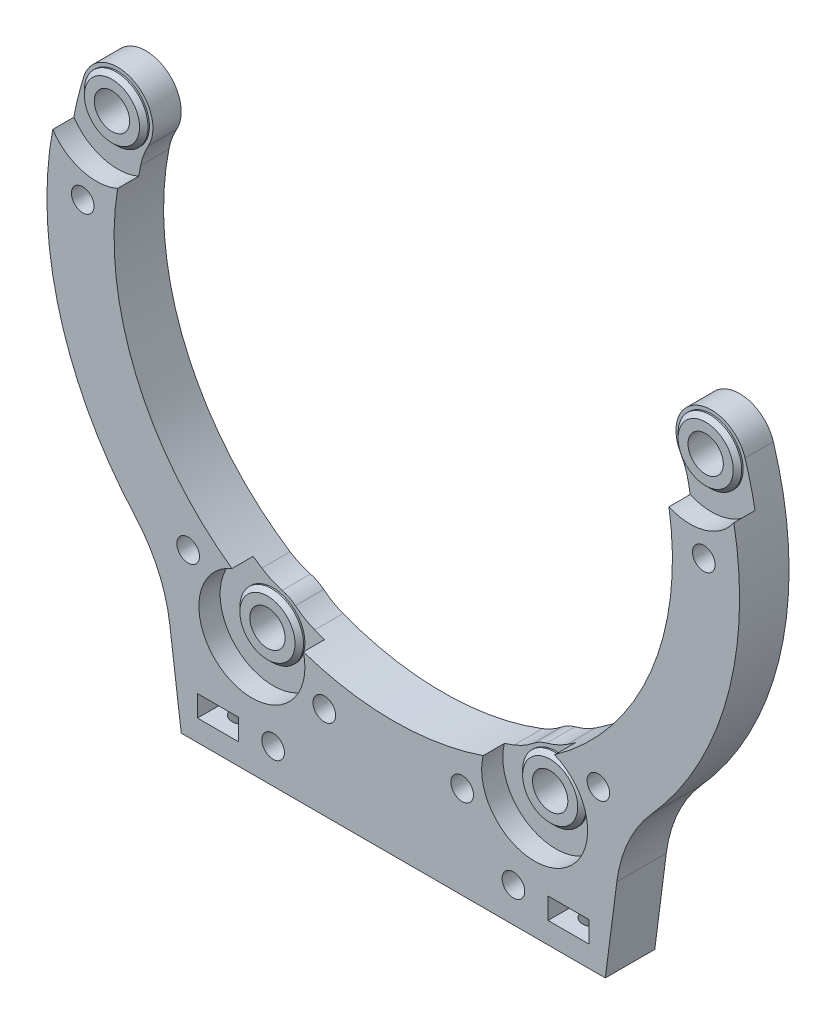
SolidWorks part; units mm, degrees
ref_plane "Front Plane" through (0, 0, 0) normal (0, 0, 1) x (1, 0, 0)
ref_plane "Top Plane" through (0, 0, 0) normal (0, 1, 0) x (1, 0, 0)
ref_plane "Right Plane" through (0, 0, 0) normal (1, 0, 0) x (0, 0, -1)
sketch "Sketch1" plane through (0, 0, 0) normal (0, 0, 1) x (1, 0, 0)
  line L0 (-74.8664, -56) -> (73.8479, -56) construction
  line L1 (-42, 13.1149) -> (42, 13.1149) construction
  line L2 (-20, -39.1918) -> (20, -39.1918) construction
  line L3 (37, 0) -> (37, 13.1149) construction
  line L4 (30, -56) -> (32.5, -36.6708)
  line L5 (-30, -56) -> (30, -56)
  line L6 (-30, -56) -> (-32.5, -36.6708)
  line L7 (0, -56) -> (0, 0) construction
  circle A0 centre (0, 0) radius 37 construction
  circle A1 centre (42, 13.1149) radius 7 construction
  circle A2 centre (-42, 13.1149) radius 7 construction
  circle A3 centre (-20, -39.1918) radius 7 construction
  circle A4 centre (20, -39.1918) radius 7 construction
  circle A5 centre (42, 13.1149) radius 5
  circle A6 centre (-42, 13.1149) radius 5
  circle A7 centre (-20, -39.1918) radius 5
  circle A8 centre (20, -39.1918) radius 5
  circle A9 centre (-42, 13.1149) radius 2.5
  circle A10 centre (42, 13.1149) radius 2.5
  circle A11 centre (20, -39.1918) radius 2.5
  circle A12 centre (-20, -39.1918) radius 2.5
  circle A13 centre (0, 0) radius 39.5
  circle A14 centre (0, 0) radius 49
  dimension "D1" = 74
  dimension "D3" = 14
  dimension "D4" = 10
  dimension "D6" = 5
  dimension "D7" = 79
  dimension "D2" = 19
  dimension "D5" = 40
  dimension "D8" = 60
  dimension "D9" = 65
extrude "Boss-Extrude1" add sketch "Sketch1" along normal blind 4 contours A6 A14 A7 A13 | A13 A6 A9 | A6 A13 | A8 A14 A5 A13 | A13 A5 A10 | A5 A13 | A13 A7 A12 | A7 A13 | A13 A8 A11 | A8 A13 | A7 A14 A8 A13 | A14 L6 L5 L4
sketch "Sketch2" plane through (0, 0, 4) normal (0, 0, 1) x (1, 0, 0)
  circle A0 centre (-42, 13.1149) radius 4.5
  circle A1 centre (-42, 13.1149) radius 2.5 construction
  circle A2 centre (-42, 13.1149) radius 2.5
  circle A3 centre (42, 13.1149) radius 4.5
  circle A4 centre (42, 13.1149) radius 2.5 construction
  circle A5 centre (42, 13.1149) radius 2.5
  circle A6 centre (-20, -39.1918) radius 2.5 construction
  circle A7 centre (-20, -39.1918) radius 2.5
  circle A8 centre (-20, -39.1918) radius 4.5
  circle A9 centre (20, -39.1918) radius 2.5 construction
  circle A10 centre (20, -39.1918) radius 2.5
  circle A11 centre (20, -39.1918) radius 4.5
  dimension "D1" = 9
extrude "Boss-Extrude2" add sketch "Sketch2" along normal blind 0.8
chamfer "Chamfer1" distance 0.6 angle 45 4 edges at (-15.5, -39.1918, 4.8) (24.5, -39.1918, 4.8) (46.5, 13.1149, 4.8) (-37.5, 13.1149, 4.8)
sketch "Sketch3" plane through (0, 0, 4) normal (0, 0, 1) x (1, 0, 0)
  line L0 (-30, -56) -> (-32.5, -36.6708) construction
  line L1 (-30, -56) -> (30, -56) construction
  line L2 (30, -56) -> (32.5, -36.6708) construction
  line L3 (-30, -56) -> (-32.5, -36.6708)
  line L4 (-30, -56) -> (30, -56)
  line L5 (30, -56) -> (32.5, -36.6708)
  circle A0 centre (-42, 13.1149) radius 7.5
  circle A1 centre (42, 13.1149) radius 7.5
  circle A2 centre (20, -39.1918) radius 7.5
  circle A3 centre (-20, -39.1918) radius 7.5
  arc A4 (32.5, -36.6708) -> (46.7727, 14.6052) centre (0, 0) ccw construction
  arc A5 (19.7687, -34.1972) -> (38.2683, 9.787) centre (0, 0) ccw construction
  arc A6 (-16.0913, -36.0738) -> (16.0913, -36.0738) centre (0, 0) ccw construction
  arc A7 (-46.7727, 14.6052) -> (-32.5, -36.6708) centre (0, 0) ccw construction
  arc A8 (-38.2683, 9.787) -> (-19.7687, -34.1972) centre (0, 0) ccw construction
  arc A9 (32.5, -36.6708) -> (46.7727, 14.6052) centre (0, 0) ccw
  arc A10 (19.7687, -34.1972) -> (38.2683, 9.787) centre (0, 0) ccw
  arc A11 (-16.0913, -36.0738) -> (16.0913, -36.0738) centre (0, 0) ccw
  arc A12 (-46.7727, 14.6052) -> (-32.5, -36.6708) centre (0, 0) ccw
  arc A13 (-38.2683, 9.787) -> (-19.7687, -34.1972) centre (0, 0) ccw
  arc M5 (38.2683, 9.787) -> (19.7687, -34.1972) centre (0, 0) cw
  arc M7 (16.0913, -36.0738) -> (-16.0913, -36.0738) centre (0, 0) cw
  arc M9 (-19.7687, -34.1972) -> (-38.2683, 9.787) centre (0, 0) cw
  arc M11 (-46.7727, 14.6052) -> (-32.5, -36.6708) centre (0, 0) ccw
  line M12 (-32.5, -36.6708) -> (-30, -56)
  line M13 (-30, -56) -> (30, -56)
  line M14 (30, -56) -> (32.5, -36.6708)
  arc M15 (32.5, -36.6708) -> (46.7727, 14.6052) centre (0, 0) ccw
  dimension "D1" = 15
extrude "Boss-Extrude3" add sketch "Sketch3" along normal blind 3 contours A3 A0 A1 A2 M9 M11 M12 M13 M14 M15 M5 M7
fillet "Fillet1" radius 10 6 edges at (-19.7687, -34.1972, 2) (-16.0913, -36.0738, 2) (16.0913, -36.0738, 2) (19.7687, -34.1972, 2) (38.2683, 9.787, 2) (-38.2683, 9.787, 2)
fillet "Fillet2" radius 20 2 edges at (32.5, -36.6708, 3.5) (-32.5, -36.6708, 3.5)
sketch "Sketch4" plane through (0, -56, 0) normal (0, -1, 0) x (1, 0, 0)
  line L4 (24.8, 10.5) -> (-24.8, 10.5)
  line L5 (24.8, 3.4) -> (24.8, 10.5)
  line L6 (-24.8, 3.4) -> (24.8, 3.4)
  line L7 (-24.8, 10.5) -> (-24.8, 3.4)
  line L8 (24.8, 10.5) -> (-24.8, 10.5) construction
  line L9 (24.8, 3.4) -> (24.8, 10.5) construction
  line L10 (-24.8, 3.4) -> (24.8, 3.4) construction
  line L11 (-24.8, 10.5) -> (-24.8, 3.4) construction
  circle A1 centre (24.8, 3.4) radius 1.6
  circle A2 centre (24.8, 3.4) radius 1.6
  circle A3 centre (-24.8, 3.4) radius 1.6
  circle A4 centre (-24.8, 3.4) radius 1.6
  circle A5 centre (24.8, 10.5) radius 1.6
  circle A6 centre (24.8, 10.5) radius 1.6 construction
  circle A7 centre (-24.8, 10.5) radius 1.6
  circle A8 centre (-24.8, 10.5) radius 1.6 construction
  dimension "D1" = 0
  dimension "D2" = 0
  dimension "D3" = 0
  dimension "D4" = 0
  dimension "D5" = 0
extrude "Cut-Extrude1" cut sketch "Sketch4" against normal blind 9
sketch "Sketch5" plane through (0, 0, 7) normal (0, 0, 1) x (1, 0, 0)
  line L5 (-27.7, -50) -> (-27.7, -53)
  line L6 (-21.9, -50) -> (-27.7, -50)
  line L7 (-21.9, -53) -> (-21.9, -50)
  line L8 (-27.7, -53) -> (-21.9, -53)
  line L9 (-27.7, -50) -> (-27.7, -53)
  line L10 (-21.9, -50) -> (-27.7, -50)
  line L11 (-21.9, -53) -> (-21.9, -50)
  line L12 (-27.7, -53) -> (-21.9, -53)
  line L13 (21.9, -50) -> (21.9, -53)
  line L14 (27.7, -50) -> (21.9, -50)
  line L15 (27.7, -53) -> (27.7, -50)
  line L16 (21.9, -53) -> (27.7, -53)
  line L17 (21.9, -50) -> (21.9, -53)
  line L18 (27.7, -50) -> (21.9, -50)
  line L19 (27.7, -53) -> (27.7, -50)
  line L20 (21.9, -53) -> (27.7, -53)
  dimension "D1" = 0
  dimension "D2" = 0
extrude "Cut-Extrude2" cut sketch "Sketch5" against normal through all
sketch "Sketch6" plane through (0, 0, 0) normal (0, 0, -1) x (-1, 0, 0)
  circle A1 centre (29.0204, -33.0729) radius 1.6
  circle A2 centre (29.0204, -33.0729) radius 1.6
  circle A3 centre (43.9351, 2.388) radius 1.6
  circle A4 centre (43.9351, 2.388) radius 1.6
  circle A5 centre (-17, -51.1) radius 1.6
  circle A6 centre (-17, -51.1) radius 1.6
  circle A7 centre (17, -51.1) radius 1.6
  circle A8 centre (17, -51.1) radius 1.6
  circle A9 centre (9.7522, -42.9056) radius 1.6
  circle A10 centre (9.7522, -42.9056) radius 1.6
  circle A11 centre (-43.9351, 2.388) radius 1.6
  circle A12 centre (-43.9351, 2.388) radius 1.6
  circle A13 centre (-29.0204, -33.0729) radius 1.6
  circle A14 centre (-29.0204, -33.0729) radius 1.6
  circle A15 centre (-9.7522, -42.9056) radius 1.6
  circle A16 centre (-9.7522, -42.9056) radius 1.6
  dimension "D1" = 0
  dimension "D2" = 0
  dimension "D3" = 0
  dimension "D4" = 0
  dimension "D5" = 0
  dimension "D6" = 0
  dimension "D7" = 0
  dimension "D8" = 0
extrude "Cut-Extrude3" cut sketch "Sketch6" against normal through all
sketch "Sketch7" plane through (0, 0, 0) normal (0, 0, -1) x (-1, 0, 0)
  line L0 (-43.9351, 2.388) -> (-42.8917, 8.1722) construction
  line L1 (-40.6397, 1.7935) -> (-41.7726, 4.9447)
  line L2 (-41.7726, 4.9447) -> (-45.068, 5.5392)
  line L3 (-45.068, 5.5392) -> (-47.2306, 2.9825)
  line L4 (-47.2306, 2.9825) -> (-46.0977, -0.1686)
  line L5 (-46.0977, -0.1686) -> (-42.8023, -0.7632)
  line L6 (-42.8023, -0.7632) -> (-40.6397, 1.7935)
  line L7 (-29.0204, -33.0729) -> (-20, -39.1918) construction
  line L8 (-27.1406, -30.3017) -> (-30.4804, -30.0593)
  line L9 (-30.4804, -30.0593) -> (-32.3603, -32.8305)
  line L10 (-32.3603, -32.8305) -> (-30.9003, -35.8441)
  line L11 (-30.9003, -35.8441) -> (-27.5604, -36.0865)
  line L12 (-27.5604, -36.0865) -> (-25.6806, -33.3152)
  line L13 (-25.6806, -33.3152) -> (-27.1406, -30.3017)
  line L14 (-8.6113, -39.7574) -> (-11.9082, -40.3434)
  line L15 (-11.9082, -40.3434) -> (-13.0491, -43.4917)
  line L16 (-13.0491, -43.4917) -> (-10.8931, -46.0539)
  line L17 (-10.8931, -46.0539) -> (-7.5962, -45.4679)
  line L18 (-7.5962, -45.4679) -> (-6.4552, -42.3196)
  line L19 (-6.4552, -42.3196) -> (-8.6113, -39.7574)
  line L20 (-14.1, -49.4257) -> (-17, -47.7514)
  line L21 (-17, -47.7514) -> (-19.9, -49.4257)
  line L22 (-19.9, -49.4257) -> (-19.9, -52.7743)
  line L23 (-19.9, -52.7743) -> (-17, -54.4486)
  line L24 (-17, -54.4486) -> (-14.1, -52.7743)
  line L25 (-14.1, -52.7743) -> (-14.1, -49.4257)
  line L26 (-20, -39.1918) -> (-9.7522, -42.9056) construction
  line L27 (-21.9, -50) -> (-21.9, -53) construction
  line L28 (0, 0) -> (0, -39.5) construction
  line L29 (20, -39.1918) -> (9.7522, -42.9056) construction
  line L30 (29.0204, -33.0729) -> (20, -39.1918) construction
  line L31 (43.9351, 2.388) -> (42.8917, 8.1722) construction
  line L32 (14.1, -52.7743) -> (14.1, -49.4257)
  line L33 (17, -54.4486) -> (14.1, -52.7743)
  line L34 (19.9, -52.7743) -> (17, -54.4486)
  line L35 (19.9, -49.4257) -> (19.9, -52.7743)
  line L36 (17, -47.7514) -> (19.9, -49.4257)
  line L37 (14.1, -49.4257) -> (17, -47.7514)
  line L38 (6.4552, -42.3196) -> (8.6113, -39.7574)
  line L39 (7.5962, -45.4679) -> (6.4552, -42.3196)
  line L40 (10.8931, -46.0539) -> (7.5962, -45.4679)
  line L41 (13.0491, -43.4917) -> (10.8931, -46.0539)
  line L42 (11.9082, -40.3434) -> (13.0491, -43.4917)
  line L43 (8.6113, -39.7574) -> (11.9082, -40.3434)
  line L44 (25.6806, -33.3152) -> (27.1406, -30.3017)
  line L45 (27.5604, -36.0865) -> (25.6806, -33.3152)
  line L46 (30.9003, -35.8441) -> (27.5604, -36.0865)
  line L47 (32.3603, -32.8305) -> (30.9003, -35.8441)
  line L48 (30.4804, -30.0593) -> (32.3603, -32.8305)
  line L49 (27.1406, -30.3017) -> (30.4804, -30.0593)
  line L50 (42.8023, -0.7632) -> (40.6397, 1.7935)
  line L51 (46.0977, -0.1686) -> (42.8023, -0.7632)
  line L52 (47.2306, 2.9825) -> (46.0977, -0.1686)
  line L53 (45.068, 5.5392) -> (47.2306, 2.9825)
  line L54 (41.7726, 4.9447) -> (45.068, 5.5392)
  line L55 (40.6397, 1.7935) -> (41.7726, 4.9447)
  arc A0 (-48.1889, 8.8785) -> (-39.0041, 6.2392) centre (-42, 13.1149) ccw construction
  arc A1 (-48.1889, 8.8785) -> (-39.0041, 6.2392) centre (-42, 13.1149) ccw construction
  circle A2 centre (-43.9351, 2.388) radius 2.9 construction
  circle A3 centre (-29.0204, -33.0729) radius 2.9 construction
  circle A4 centre (-9.7522, -42.9056) radius 2.9 construction
  circle A5 centre (-17, -51.1) radius 2.9 construction
  arc A6 (-22.8191, -32.2418) -> (-12.718, -37.3965) centre (-20, -39.1918) ccw construction
  arc A7 (-22.8191, -32.2418) -> (-12.718, -37.3965) centre (-20, -39.1918) ccw construction
  arc A8 (-14.1073, -36.8949) -> (14.1073, -36.8949) centre (0, 0) ccw construction
  arc A9 (22.8191, -32.2418) -> (12.718, -37.3965) centre (20, -39.1918) cw construction
  circle A10 centre (17, -51.1) radius 2.9 construction
  circle A11 centre (9.7522, -42.9056) radius 2.9 construction
  circle A12 centre (29.0204, -33.0729) radius 2.9 construction
  circle A13 centre (43.9351, 2.388) radius 2.9 construction
  arc A14 (48.1889, 8.8785) -> (39.0041, 6.2392) centre (42, 13.1149) cw construction
  dimension "D1" = 5.8
extrude "Cut-Extrude4" cut sketch "Sketch7" against normal blind 2.5
sketch "Sketch8" plane through (0, 0, 2.5) normal (0, 0, -1) x (-1, 0, 0)
  circle A0 centre (43.9351, 2.388) radius 1.6 construction
  circle A1 centre (29.0204, -33.0729) radius 1.6 construction
  circle A2 centre (17, -51.1) radius 1.6 construction
  circle A3 centre (9.7522, -42.9056) radius 1.6 construction
  circle A4 centre (-17, -51.1) radius 1.6 construction
  circle A5 centre (-9.7522, -42.9056) radius 1.6 construction
  circle A6 centre (-29.0204, -33.0729) radius 1.6 construction
  circle A7 centre (-43.9351, 2.388) radius 1.6 construction
  circle A8 centre (43.9351, 2.388) radius 1.6
  circle A9 centre (29.0204, -33.0729) radius 1.6
  circle A10 centre (17, -51.1) radius 1.6
  circle A11 centre (9.7522, -42.9056) radius 1.6
  circle A12 centre (-17, -51.1) radius 1.6
  circle A13 centre (-9.7522, -42.9056) radius 1.6
  circle A14 centre (-29.0204, -33.0729) radius 1.6
  circle A15 centre (-43.9351, 2.388) radius 1.6
extrude "Boss-Extrude4" add sketch "Sketch8" against normal blind 0.3
